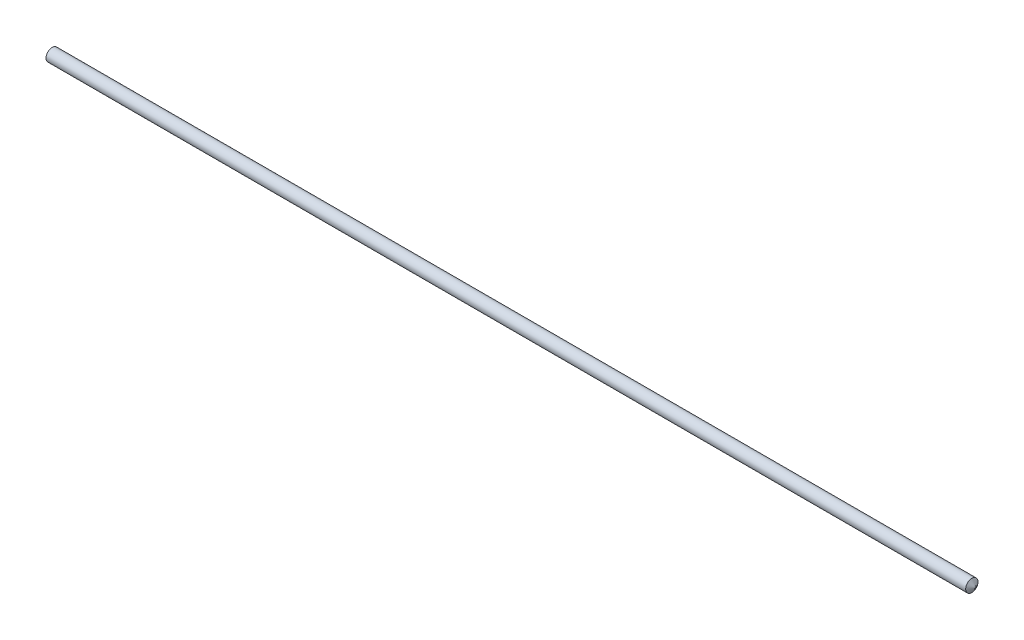
SolidWorks part; units mm, degrees
ref_plane "Front Plane" through (0, 0, 0) normal (0, 0, 1) x (1, 0, 0)
ref_plane "Top Plane" through (0, 0, 0) normal (0, 1, 0) x (1, 0, 0)
ref_plane "Right Plane" through (0, 0, 0) normal (1, 0, 0) x (0, 0, -1)
sketch "Sketch15" plane through (0, 0, 0) normal (0, 1, 0) x (1, 0, 0)
  line L0 (0, 0) -> (150, 0) construction
  line L1 (0, 0) -> (0.6009, 1)
  line L2 (0.6009, 1) -> (149.3991, 1)
  line L3 (149.3991, 1) -> (150, 0)
  line L4 (0, 0) -> (150, 0)
  dimension "D1" = 59
  dimension "D2" = 59
  dimension "D3" = 150
  dimension "D4" = 2
revolve "Revolve1" add sketch "Sketch15" angle 360 about L0
